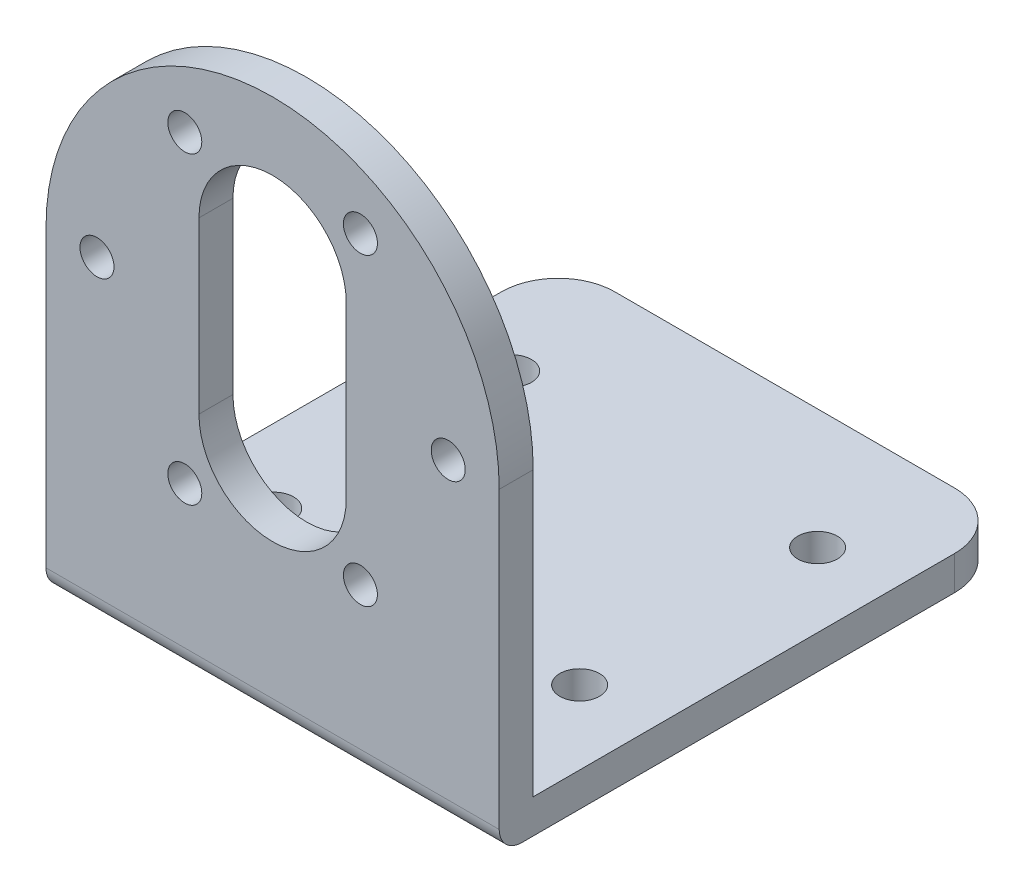
SolidWorks part; units mm, degrees
ref_plane "Alzado" through (0, 0, 0) normal (0, 0, 1) x (1, 0, 0)
ref_plane "Planta" through (0, 0, 0) normal (0, 1, 0) x (1, 0, 0)
ref_plane "Vista lateral" through (0, 0, 0) normal (1, 0, 0) x (0, 0, -1)
sketch "Croquis1" plane through (0, 0, 0) normal (0, 0, 1) x (1, 0, 0)
  line L0 (-30.926, 4) -> (33.5245, 4) construction
  line L1 (-20, -24) -> (20, -24)
  line L2 (-20, -24) -> (-20, 4)
  line L4 (20, -24) -> (20, 4)
  line L5 (-36.9898, 0) -> (44.9202, 0) construction
  line L6 (0, 4) -> (-15.5, 4) construction
  line L7 (0, 34.1401) -> (0, -31.2366) construction
  arc A0 (-20, 4) -> (20, 4) centre (0, 4) cw
  circle A1 centre (0, 4) radius 15.5 construction
  circle A2 centre (-15.5, 4) radius 1.5
  circle A3 centre (-7.75, 17.4234) radius 1.5
  circle A4 centre (7.75, 17.4234) radius 1.5
  circle A5 centre (15.5, 4) radius 1.5
  circle A6 centre (7.75, -9.4234) radius 1.5
  circle A7 centre (-7.75, -9.4234) radius 1.5
  point P0 (0, 0)
  dimension "D3" = 20
  dimension "D4" = 31
  dimension "D6" = 3
  dimension "D1" = 40
  dimension "D2" = 4
  dimension "D5" = 28
  dimension "D8" = 15.5
  dimension "D7" = 6
extrude "Saliente-Extruir1" add sketch "Croquis1" along normal mid plane 3
sketch "Croquis2" plane through (0, 0, 1.5) normal (0, 0, 1) x (1, 0, 0)
  line L0 (-27.0438, 4) -> (27.4972, 4) construction
  line L1 (0, 28.3189) -> (0, -31.6575) construction
  line L3 (-20, 4) -> (-20, -24)
  line L4 (-20, -24) -> (20, -24)
  line L5 (20, -24) -> (20, 4)
  line L6 (-20, 4) -> (-20, -24)
  line L7 (-20, -24) -> (20, -24)
  line L8 (20, -24) -> (20, 4)
  line L12 (0, 11.5) -> (0, -3.5) construction
  line L13 (6.5, 11.5) -> (6.5, -3.5)
  line L14 (-6.5, 11.5) -> (-6.5, -3.5)
  arc A1 (20, 4) -> (-20, 4) centre (0, 4) ccw
  arc A2 (20, 4) -> (-20, 4) centre (0, 4) ccw
  arc A3 (6.5, 11.5) -> (-6.5, 11.5) centre (0, 11.5) ccw
  arc A4 (-6.5, -3.5) -> (6.5, -3.5) centre (0, -3.5) ccw
  point P9 (0, 4)
  dimension "D3" = 15
  dimension "D2" = 13
  dimension "D1" = 0
extrude "Cortar-Extruir3" cut sketch "Croquis2" against normal blind 3 contours L14 A3 L13 A4
sketch "Croquis3" plane through (0, 0, -1.5) normal (0, 0, -1) x (-1, 0, 0)
  line L0 (20, 4) -> (20, -24) construction
  line L1 (-20, -24) -> (20, -24)
  line L2 (-20, -24) -> (-20, -21)
  line L3 (-20, -21) -> (20, -21)
  line L4 (20, -24) -> (20, -21)
  dimension "D1" = 3
extrude "Saliente-Extruir2" add sketch "Croquis3" along normal blind 42.2
sketch "Croquis4" plane through (0, -21, 0) normal (0, 1, 0) x (1, 0, 0)
  line L0 (23.7911, 22.6) -> (-31.4497, 22.6) construction
  line L1 (0, 51.3817) -> (0, -12.734) construction
  line L4 (-20, 1.5) -> (20, 1.5)
  line L5 (20, 1.5) -> (20, 43.7)
  line L6 (20, 43.7) -> (-20, 43.7)
  line L7 (-20, 43.7) -> (-20, 1.5)
  line L8 (-20, 1.5) -> (20, 1.5)
  line L9 (20, 1.5) -> (20, 43.7)
  line L10 (20, 43.7) -> (-20, 43.7)
  line L11 (-20, 43.7) -> (-20, 1.5)
  circle A0 centre (-13.5, 33.1) radius 1.75
  circle A1 centre (13.5, 33.1) radius 1.75
  circle A2 centre (13.5, 12.1) radius 1.75
  circle A3 centre (-13.5, 12.1) radius 1.75
  point P11 (20, 22.6)
  dimension "D3" = 3.5
  dimension "D2" = 10.5
  dimension "D4" = 13.5
  dimension "D7" = 13.5
  dimension "D8" = 10.5
  dimension "D9" = 13.5
  dimension "D1" = 0
  dimension "D5" = 2
  dimension "D6" = 2
extrude "Cortar-Extruir5" cut sketch "Croquis4" against normal blind 42.2 contours A0 | A1 | A2 | A3
fillet "Redondeo1" radius 2 1 edges at (0, -24, 1.5)
fillet "Redondeo2" radius 5 2 edges at (-20, -22.5, -43.7) (20, -22.5, -43.7)
sketch "Croquis5" plane through (0, -21, 0) normal (0, 1, 0) x (1, 0, 0)
  line L5 (15, 43.7) -> (-15, 43.7)
  line L6 (-20, 38.7) -> (-20, 1.5)
  line L7 (-20, 1.5) -> (20, 1.5)
  line L8 (20, 1.5) -> (20, 38.7)
  line L9 (15, 43.7) -> (-15, 43.7)
  line L10 (-20, 38.7) -> (-20, 1.5)
  line L11 (-20, 1.5) -> (20, 1.5)
  line L12 (20, 1.5) -> (20, 38.7)
  line L13 (20, 1.5) -> (-20, 1.5)
  line L14 (-20, 1.5) -> (-20, -1.5)
  line L15 (-20, -1.5) -> (20, -1.5)
  line L16 (20, -1.5) -> (20, 1.5)
  line L17 (20, 1.5) -> (-20, 1.5)
  line L18 (-20, 1.5) -> (-20, -1.5)
  line L19 (-20, -1.5) -> (20, -1.5)
  line L20 (20, -1.5) -> (20, 1.5)
  arc A2 (-15, 43.7) -> (-20, 38.7) centre (-15, 38.7) ccw
  arc A3 (20, 38.7) -> (15, 43.7) centre (15, 38.7) ccw
  arc A4 (-15, 43.7) -> (-20, 38.7) centre (-15, 38.7) ccw
  arc A5 (20, 38.7) -> (15, 43.7) centre (15, 38.7) ccw
  dimension "D1" = 0
  dimension "D2" = 0
